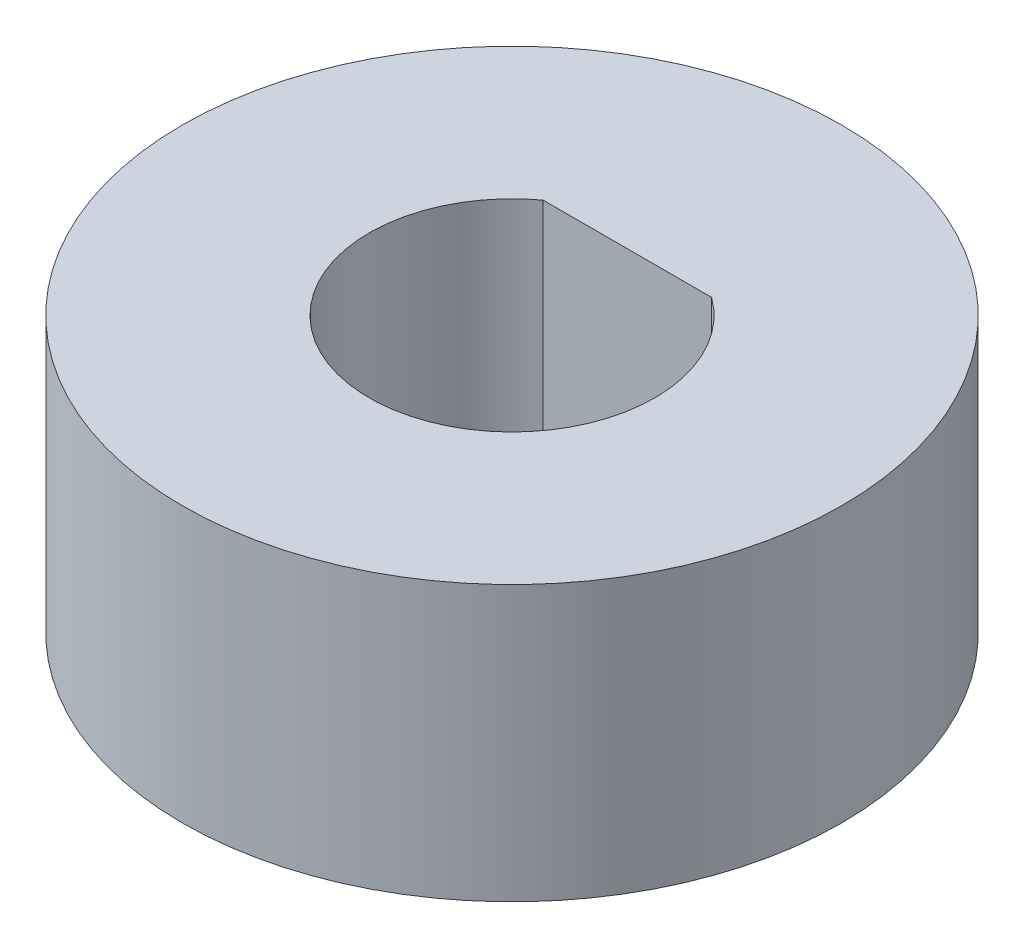
SolidWorks part; units mm, degrees
ref_plane "Front Plane" through (0, 0, 0) normal (0, 0, 1) x (1, 0, 0)
ref_plane "Top Plane" through (0, 0, 0) normal (0, 1, 0) x (1, 0, 0)
ref_plane "Right Plane" through (0, 0, 0) normal (1, 0, 0) x (0, 0, -1)
sketch "Sketch1" plane through (0, 0, 0) normal (0, 1, 0) x (1, 0, 0)
  line L0 (1.5492, 2.15) -> (-1.5492, 2.15)
  line L1 (0, 2) -> (1.5, 2)
  line L2 (1.5, 2) -> (0, 2)
  line L3 (1.5, 2) -> (-1.5, 2) construction
  arc A0 (-1.5, 2) -> (1.5, 2) centre (0, 0) ccw
  arc A1 (-1.5492, 2.15) -> (1.5492, 2.15) centre (0, 0) ccw
  circle A2 centre (0, 0) radius 6
  dimension "D1" = 0.15
extrude "Boss-Extrude1" add sketch "Sketch1" along normal blind 5 contours A2 A1 L0
sketch "Sketch2" plane through (0, 5, 0) normal (0, 1, 0) x (1, 0, 0)
  line L0 (1.5264, 2.08) -> (-1.5264, 2.08)
  line L1 (1.5492, 2.15) -> (-1.5492, 2.15)
  line L2 (1.5492, 2.15) -> (-1.5492, 2.15)
  arc A0 (-1.5264, 2.08) -> (1.5264, 2.08) centre (0, 0) ccw
  arc A1 (-1.5492, 2.15) -> (1.5492, 2.15) centre (0, 0) ccw
  arc A2 (-1.5492, 2.15) -> (1.5492, 2.15) centre (0, 0) ccw
  dimension "D1" = 0
  dimension "D2" = 0.07
extrude "Boss-Extrude2" add sketch "Sketch2" against normal up to surface (5 mm away) up to face at (0, 0, 0.25)
sketch "Sketch3" plane through (0, 5, 0) normal (0, 1, 0) x (1, 0, 0)
  line L3 (1.533, 2.1) -> (-1.533, 2.1)
  line L4 (1.533, 2.1) -> (-1.533, 2.1)
  arc A2 (-1.533, 2.1) -> (1.533, 2.1) centre (0, 0) ccw
  arc A3 (-1.533, 2.1) -> (1.533, 2.1) centre (0, 0) ccw
  dimension "D1" = 0.02
extrude "Cut-Extrude1" cut sketch "Sketch3" against normal blind 5
